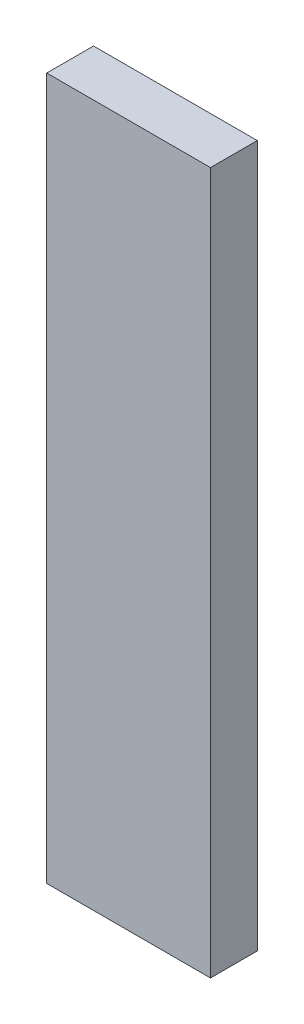
SolidWorks part; units mm, degrees
material "Natural Rubber"
ref_plane "Front Plane" through (0, 0, 0) normal (0, 0, 1) x (1, 0, 0)
ref_plane "Top Plane" through (0, 0, 0) normal (0, 1, 0) x (1, 0, 0)
ref_plane "Right Plane" through (0, 0, 0) normal (1, 0, 0) x (0, 0, -1)
sketch "Sketch1" plane through (0, 0, 0) normal (0, 0, 1) x (1, 0, 0)
  line L1 (-5.25, 22.5) -> (5.25, 22.5)
  line L2 (-5.25, 22.5) -> (-5.25, -22.5)
  line L3 (-5.25, -22.5) -> (5.25, -22.5)
  line L4 (5.25, 22.5) -> (5.25, -22.5)
  line L5 (-5.25, 22.5) -> (5.25, -22.5) construction
  line L6 (-5.25, -22.5) -> (5.25, 22.5) construction
  point P0 (0, 0)
  dimension "D1" = 45
  dimension "D2" = 10.5
extrude "Boss-Extrude1" add sketch "Sketch1" against normal blind 3
